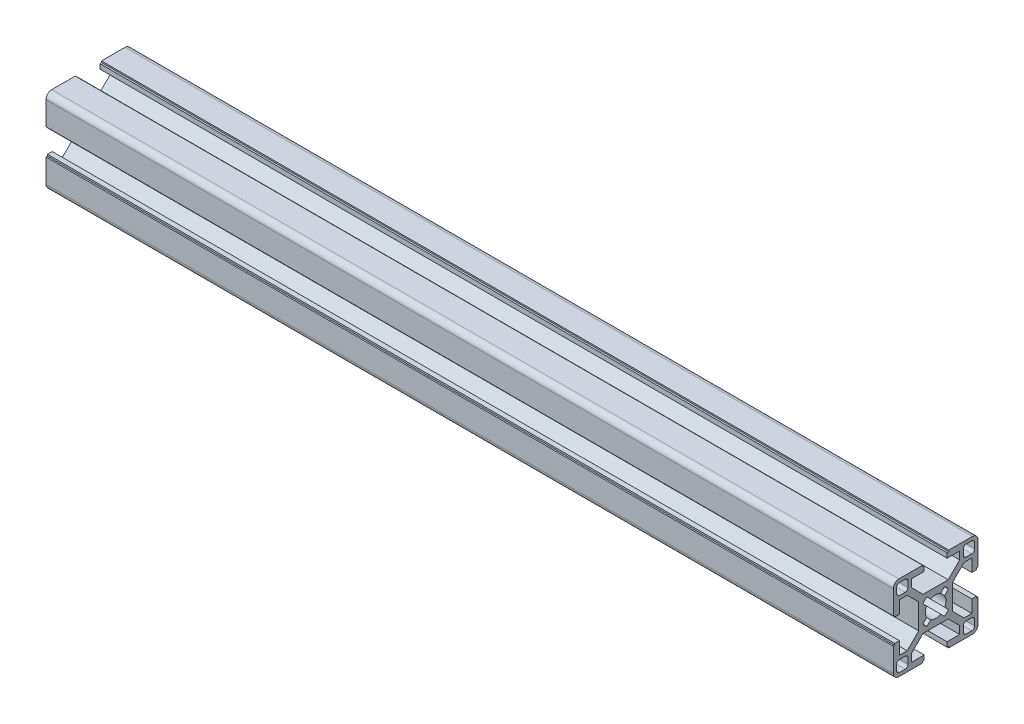
SolidWorks part; units mm, degrees
material "1060 Alloy"
ref_plane "Ebene vorne" through (0, 0, 0) normal (0, 0, 1) x (1, 0, 0)
ref_plane "Ebene oben" through (0, 0, 0) normal (0, 1, 0) x (1, 0, 0)
ref_plane "Ebene rechts" through (0, 0, 0) normal (1, 0, 0) x (0, 0, -1)
sketch "Skizze1" plane through (0, 0, 0) normal (1, 0, 0) x (0, 0, -1)
  line L0 (8.5, 10.0556) -> (4.4444, 6)
  line L1 (13, 15) -> (-13, 15)
  line L2 (15, 13) -> (15, -13)
  line L3 (13, -15) -> (-13, -15)
  line L4 (-15, 13) -> (-15, -13)
  line L5 (15, 15) -> (-15, -15) construction
  line L6 (15, -15) -> (-15, 15) construction
  line L7 (6, 6) -> (-6, 6)
  line L8 (6, 6) -> (6, -6)
  line L9 (6, -6) -> (-6, -6)
  line L10 (-6, 6) -> (-6, -6)
  line L11 (6, 6) -> (-6, -6) construction
  line L12 (6, -6) -> (-6, 6) construction
  line L13 (8.5, 12.8) -> (-8.5, 12.8)
  line L14 (8.5, 12.8) -> (8.5, 6)
  line L15 (8.5, 6) -> (-8.5, 6)
  line L16 (-8.5, 12.8) -> (-8.5, 6)
  line L17 (4.05, 15) -> (-4.05, 15)
  line L18 (4.05, 15) -> (4.05, 12.8)
  line L19 (4.05, 12.8) -> (-4.05, 12.8)
  line L20 (-4.05, 15) -> (-4.05, 12.8)
  line L21 (-8.5, 10.0556) -> (-4.4444, 6)
  line L22 (3.1172, 4.5314) -> (1.7751, 3.1893)
  line L23 (-3.1172, 4.5314) -> (-1.7751, 3.1893)
  line L24 (15, -4.05) -> (12.8, -4.05)
  line L25 (4.05, 15) -> (4.6516, 15)
  line L26 (4.05, 15) -> (4.05, 14.5)
  line L27 (4.05, 14.5) -> (4.6516, 14.5)
  line L28 (4.6516, 15) -> (4.6516, 14.5)
  line L29 (-4.05, 15) -> (-4.6516, 15)
  line L30 (-4.05, 15) -> (-4.05, 14.5)
  line L31 (-4.05, 14.5) -> (-4.6516, 14.5)
  line L32 (-4.6516, 15) -> (-4.6516, 14.5)
  line L33 (15, -4.6516) -> (14.5, -4.6516)
  line L34 (14.5, -4.05) -> (14.5, -4.6516)
  line L35 (14.5, 4.05) -> (14.5, 4.6516)
  line L36 (15, 4.6516) -> (14.5, 4.6516)
  line L37 (15, 4.05) -> (12.8, 4.05)
  line L38 (12.8, 8.5) -> (6, 8.5)
  line L39 (12.8, -8.5) -> (12.8, 8.5)
  line L40 (12.8, -8.5) -> (6, -8.5)
  line L41 (10.0556, -8.5) -> (6, -4.4444)
  line L42 (10.0556, 8.5) -> (6, 4.4444)
  line L43 (4.5314, -3.1172) -> (3.1893, -1.7751)
  line L44 (4.5314, 3.1172) -> (3.1893, 1.7751)
  line L45 (-4.05, -15) -> (-4.05, -12.8)
  line L46 (-4.6516, -15) -> (-4.6516, -14.5)
  line L47 (-4.05, -14.5) -> (-4.6516, -14.5)
  line L48 (4.05, -14.5) -> (4.6516, -14.5)
  line L49 (4.6516, -15) -> (4.6516, -14.5)
  line L50 (4.05, -15) -> (4.05, -12.8)
  line L51 (8.5, -12.8) -> (8.5, -6)
  line L52 (-8.5, -12.8) -> (8.5, -12.8)
  line L53 (-8.5, -12.8) -> (-8.5, -6)
  line L54 (-8.5, -10.0556) -> (-4.4444, -6)
  line L55 (8.5, -10.0556) -> (4.4444, -6)
  line L56 (-3.1172, -4.5314) -> (-1.7751, -3.1893)
  line L57 (3.1172, -4.5314) -> (1.7751, -3.1893)
  line L58 (-15, 4.05) -> (-12.8, 4.05)
  line L59 (-15, 4.6516) -> (-14.5, 4.6516)
  line L60 (-14.5, 4.05) -> (-14.5, 4.6516)
  line L61 (-14.5, -4.05) -> (-14.5, -4.6516)
  line L62 (-15, -4.6516) -> (-14.5, -4.6516)
  line L63 (-15, -4.05) -> (-12.8, -4.05)
  line L64 (-12.8, -8.5) -> (-6, -8.5)
  line L65 (-12.8, 8.5) -> (-12.8, -8.5)
  line L66 (-12.8, 8.5) -> (-6, 8.5)
  line L67 (-10.0556, 8.5) -> (-6, 4.4444)
  line L68 (-10.0556, -8.5) -> (-6, -4.4444)
  line L69 (-4.5314, 3.1172) -> (-3.1893, 1.7751)
  line L70 (-4.5314, -3.1172) -> (-3.1893, -1.7751)
  line L71 (6, -8.5) -> (6, 8.5)
  line L72 (-8.5, -6) -> (8.5, -6)
  line L73 (-6, 8.5) -> (-6, -8.5)
  line L75 (12.8, 13.8) -> (10.8, 13.8)
  line L76 (13.8, 12.8) -> (13.8, 10.8)
  line L77 (12.8, 9.8) -> (10.8, 9.8)
  line L78 (9.8, 12.8) -> (9.8, 10.8)
  line L79 (13.8, 13.8) -> (9.8, 9.8) construction
  line L80 (13.8, 9.8) -> (9.8, 13.8) construction
  line L81 (-10.8, 13.8) -> (-12.8, 13.8)
  line L82 (-9.8, 12.8) -> (-9.8, 10.8)
  line L83 (-10.8, 9.8) -> (-12.8, 9.8)
  line L84 (-13.8, 12.8) -> (-13.8, 10.8)
  line L85 (-9.8, 13.8) -> (-13.8, 9.8) construction
  line L86 (-9.8, 9.8) -> (-13.8, 13.8) construction
  line L87 (12.8, -9.8) -> (10.8, -9.8)
  line L88 (13.8, -10.8) -> (13.8, -12.8)
  line L89 (12.8, -13.8) -> (10.8, -13.8)
  line L90 (9.8, -10.8) -> (9.8, -12.8)
  line L91 (13.8, -9.8) -> (9.8, -13.8) construction
  line L92 (13.8, -13.8) -> (9.8, -9.8) construction
  line L93 (-10.8, -9.8) -> (-12.8, -9.8)
  line L94 (-9.8, -10.8) -> (-9.8, -12.8)
  line L95 (-10.8, -13.8) -> (-12.8, -13.8)
  line L96 (-13.8, -10.8) -> (-13.8, -12.8)
  line L97 (-9.8, -9.8) -> (-13.8, -13.8) construction
  line L98 (-9.8, -13.8) -> (-13.8, -9.8) construction
  arc A0 (13, -15) -> (15, -13) centre (13, -13) ccw
  arc A1 (-13, -15) -> (-15, -13) centre (-13, -13) cw
  arc A2 (-15, 13) -> (-13, 15) centre (-13, 13) cw
  arc A3 (13, 15) -> (15, 13) centre (13, 13) cw
  circle A4 centre (0, 0) radius 3.65
  circle A5 centre (0, 0) radius 5.5
  circle A6 centre (0, 0) radius 3.65
  circle A7 centre (0, 0) radius 3.65
  circle A8 centre (0, 0) radius 3.65
  arc A9 (12.8, -13.8) -> (13.8, -12.8) centre (12.8, -12.8) ccw
  arc A10 (13.8, -10.8) -> (12.8, -9.8) centre (12.8, -10.8) ccw
  arc A11 (9.8, -12.8) -> (10.8, -13.8) centre (10.8, -12.8) ccw
  arc A12 (9.8, -10.8) -> (10.8, -9.8) centre (10.8, -10.8) cw
  arc A13 (-10.8, -13.8) -> (-9.8, -12.8) centre (-10.8, -12.8) ccw
  arc A14 (-10.8, -9.8) -> (-9.8, -10.8) centre (-10.8, -10.8) cw
  arc A15 (-13.8, -12.8) -> (-12.8, -13.8) centre (-12.8, -12.8) ccw
  arc A16 (-13.8, -10.8) -> (-12.8, -9.8) centre (-12.8, -10.8) cw
  arc A17 (-12.8, 9.8) -> (-13.8, 10.8) centre (-12.8, 10.8) cw
  arc A18 (-10.8, 9.8) -> (-9.8, 10.8) centre (-10.8, 10.8) ccw
  arc A19 (-13.8, 12.8) -> (-12.8, 13.8) centre (-12.8, 12.8) cw
  arc A20 (-10.8, 13.8) -> (-9.8, 12.8) centre (-10.8, 12.8) cw
  arc A21 (13.8, 10.8) -> (12.8, 9.8) centre (12.8, 10.8) cw
  arc A22 (10.8, 9.8) -> (9.8, 10.8) centre (10.8, 10.8) cw
  arc A23 (10.8, 13.8) -> (9.8, 12.8) centre (10.8, 12.8) ccw
  arc A24 (12.8, 13.8) -> (13.8, 12.8) centre (12.8, 12.8) cw
  point P0 (0, 0)
  point P33 (0, 12.8)
  point P34 (0, 15)
  point P36 (0, 12.8)
  point P50 (11.8, 11.8)
  point P122 (0, 0)
  point P125 (-11.8, 11.8)
  point P129 (0, 0)
  point P131 (11.8, -11.8)
  point P136 (-11.8, -11.8)
  dimension "D2" = 2
  dimension "D3" = 7.3
  dimension "D4" = 11
  dimension "D20" = 1
  dimension "D1" = 30
  dimension "D5" = 12
  dimension "D6" = 17
  dimension "D7" = 8.1
  dimension "D8" = 2.2
  dimension "D9" = 9
  dimension "D10" = 1.1
  dimension "D11" = 1.1
  dimension "D12" = 1
  dimension "D13" = 1
  dimension "D14" = 0.5
  dimension "D15" = 0.6016
  dimension "D18" = 4
  dimension "D19" = 1.2
  dimension "D16" = 4
  dimension "D17" = 4
extrude "Aufsatz-Linear austragen1" add sketch "Skizze1" along normal blind 400 contours A3 L1 L28 L27 L18 L13 L14 L38 L39 L37 L35 L36 L2 | L42 L38 L14 | L71 L15 L42 L14 L38 L0 | L42 L15 L8 | L7 L71 L0 | L38 L14 L0 | L7 L15 L10 L9 L8 A5 | L43 A5 L44 A4 | L22 A5 L23 A4 | L69 A5 L70 A4 | L56 A5 L57 A4 | L3 A0 L2 L33 L34 L24 L39 L40 L51 L52 L50 L48 L49 | L51 L40 L41 | L72 L71 L55 L40 L51 L41 | L8 L72 L41 | L55 L71 L9 | L55 L51 L40 | L73 L72 L68 L53 L64 L54 | L68 L72 L10 | L9 L73 L54 | L68 L64 L53 | L64 L53 L54 | A1 L3 L46 L47 L45 L52 L53 L64 L65 L63 L61 L62 L4 | A2 L4 L59 L60 L58 L65 L66 L16 L13 L20 L31 L32 L1 | L66 L67 L16 | L16 L66 L21 | L73 L21 L66 L16 L67 L15 | L21 L73 L15 | L15 L67 L10
scale "Scale1" scale about centroid uniform scaling no x scale factor 1 y scale factor 1.333333 z scale factor 1.333333
